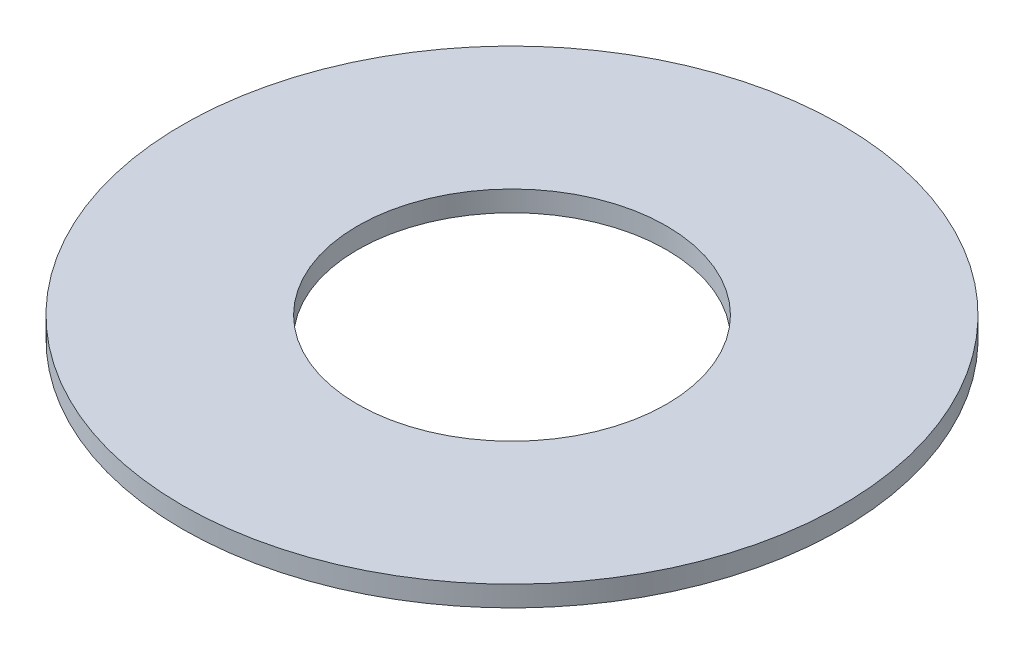
SolidWorks part; units mm, degrees
ref_plane "Płaszczyzna przednia" through (0, 0, 0) normal (0, 0, 1) x (1, 0, 0)
ref_plane "Płaszczyzna górna" through (0, 0, 0) normal (0, 1, 0) x (1, 0, 0)
ref_plane "Płaszczyzna prawa" through (0, 0, 0) normal (1, 0, 0) x (0, 0, -1)
sketch "Szkic1" plane through (0, 0, 0) normal (0, 1, 0) x (1, 0, 0)
  circle A0 centre (0, 0) radius 16
  circle A1 centre (0, 0) radius 7.5
  dimension "D1" = 32
  dimension "D2" = 15
extrude "Dodanie-wyciągnięcie1" add sketch "Szkic1" along normal blind 1
